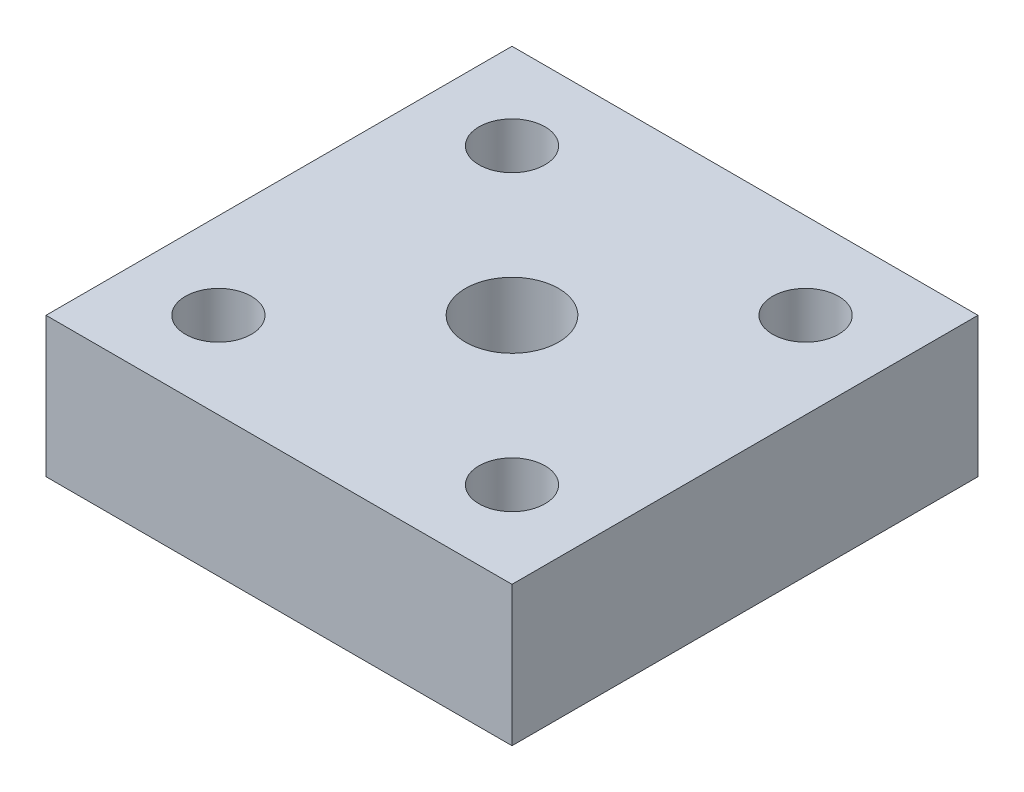
SolidWorks part; units mm, degrees
material "6061 Alloy"
ref_plane "Front Plane" through (0, 0, 0) normal (0, 0, 1) x (1, 0, 0)
ref_plane "Top Plane" through (0, 0, 0) normal (0, 1, 0) x (1, 0, 0)
ref_plane "Right Plane" through (0, 0, 0) normal (1, 0, 0) x (0, 0, -1)
sketch "Sketch1" plane through (0, 0, 0) normal (0, 1, 0) x (1, 0, 0)
  line L1 (-36.1957, 19.8882) -> (27.3043, 19.8882)
  line L2 (-36.1957, 19.8882) -> (-36.1957, -43.6118)
  line L3 (-36.1957, -43.6118) -> (27.3043, -43.6118)
  line L4 (27.3043, 19.8882) -> (27.3043, -43.6118)
  circle A0 centre (-4.4457, -11.8618) radius 6.35
  dimension "D3" = 12.7
  dimension "D1" = 63.5
  dimension "D2" = 63.5
extrude "Boss-Extrude1" add sketch "Sketch1" along normal blind 19.05
sketch "Sketch3" plane through (0, 0, 0) normal (0, 1, 0) x (1, 0, 0)
  line L1 (-24.4482, -31.8643) -> (15.5568, -31.8643) construction
  line L2 (-24.4482, -31.8643) -> (-24.4482, 8.1407) construction
  line L3 (-24.4482, 8.1407) -> (15.5568, 8.1407) construction
  line L4 (15.5568, -31.8643) -> (15.5568, 8.1407) construction
  line L5 (-24.4482, -31.8643) -> (15.5568, 8.1407) construction
  line L6 (-24.4482, 8.1407) -> (15.5568, -31.8643) construction
  circle A0 centre (-24.4482, 8.1407) radius 4.4958
  circle A1 centre (15.5568, 8.1407) radius 4.4958
  circle A2 centre (15.5568, -31.8643) radius 4.4958
  circle A3 centre (-24.4482, -31.8643) radius 4.4958
  point P0 (-4.4457, -11.8618)
  dimension "D3" = 8.9916
  dimension "D1" = 40.005
  dimension "D2" = 40.005
extrude "Cut-Extrude2" cut sketch "Sketch3" along normal blind 19.05
